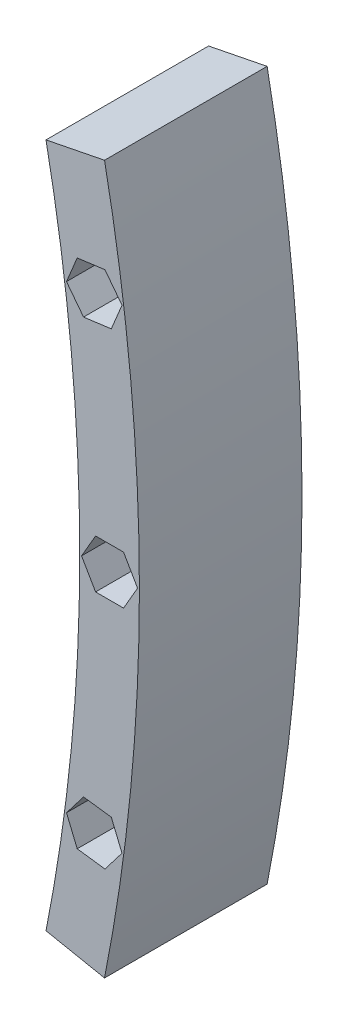
SolidWorks part; units mm, degrees
ref_plane "Front Plane" through (0, 0, 0) normal (0, 0, 1) x (1, 0, 0)
ref_plane "Top Plane" through (0, 0, 0) normal (0, 1, 0) x (1, 0, 0)
ref_plane "Right Plane" through (0, 0, 0) normal (1, 0, 0) x (0, 0, -1)
sketch "Sketch1" plane through (0, 0, 0) normal (0, 0, 1) x (1, 0, 0)
  line L0 (0, 0) -> (226.8966, 0) construction
  line L1 (240, 0) -> (240, 13.4502) construction
  line L2 (239.3239, -47.477) -> (231.4776, -45.9163)
  line L3 (239.3239, 47.477) -> (231.4776, 45.9163)
  line L4 (239.2751, -47.7222) -> (231.4289, -46.1615) construction
  line L5 (202.9378, -135.4484) -> (196.286, -131.0038) construction
  line L6 (202.7989, -135.6562) -> (196.1471, -131.2117) construction
  line L7 (135.6562, -202.7989) -> (131.2117, -196.1471) construction
  line L8 (135.4484, -202.9378) -> (131.0038, -196.286) construction
  line L9 (47.7222, -239.2751) -> (46.1615, -231.4289) construction
  line L10 (47.477, -239.3239) -> (45.9163, -231.4776) construction
  line L11 (-47.477, -239.3239) -> (-45.9163, -231.4776) construction
  line L12 (-47.7222, -239.2751) -> (-46.1615, -231.4289) construction
  line L13 (-135.4484, -202.9378) -> (-131.0038, -196.286) construction
  line L14 (-135.6562, -202.7989) -> (-131.2117, -196.1471) construction
  line L15 (-202.7989, -135.6562) -> (-196.1471, -131.2117) construction
  line L16 (-202.9378, -135.4484) -> (-196.286, -131.0038) construction
  line L17 (-239.2751, -47.7222) -> (-231.4289, -46.1615) construction
  line L18 (-239.3239, -47.477) -> (-231.4776, -45.9163) construction
  line L19 (-239.3239, 47.477) -> (-231.4776, 45.9163) construction
  line L20 (-239.2751, 47.7222) -> (-231.4289, 46.1615) construction
  line L21 (-202.9378, 135.4484) -> (-196.286, 131.0038) construction
  line L22 (-202.7989, 135.6562) -> (-196.1471, 131.2117) construction
  line L23 (-135.6562, 202.7989) -> (-131.2117, 196.1471) construction
  line L24 (-135.4484, 202.9378) -> (-131.0038, 196.286) construction
  line L25 (-47.7222, 239.2751) -> (-46.1615, 231.4289) construction
  line L26 (-47.477, 239.3239) -> (-45.9163, 231.4776) construction
  line L27 (47.477, 239.3239) -> (45.9163, 231.4776) construction
  line L28 (47.7222, 239.2751) -> (46.1615, 231.4289) construction
  line L29 (135.4484, 202.9378) -> (131.0038, 196.286) construction
  line L30 (135.6562, 202.7989) -> (131.2117, 196.1471) construction
  line L31 (202.7989, 135.6562) -> (196.1471, 131.2117) construction
  line L32 (202.9378, 135.4484) -> (196.286, 131.0038) construction
  line L33 (239.2751, 47.7222) -> (231.4289, 46.1615) construction
  line L34 (237.9468, -31.3263) -> (240, 0) construction
  line L35 (236, 0) -> (244, 0) construction
  line L36 (236.8421, 28.6593) -> (235.0847, 30.9495) construction
  line L37 (237.1132, 0) -> (238.5566, -2.5) construction
  line L38 (238.5566, -2.5) -> (241.4434, -2.5) construction
  line L39 (241.4434, -2.5) -> (242.8868, 0) construction
  line L40 (242.8868, 0) -> (241.4434, 2.5) construction
  line L41 (241.4434, 2.5) -> (238.5566, 2.5) construction
  line L42 (238.5566, 2.5) -> (237.1132, 0) construction
  line L43 (235.0847, -30.9495) -> (236.1894, -33.6165) construction
  line L44 (236.1894, -33.6165) -> (239.0515, -33.9933) construction
  line L45 (239.0515, -33.9933) -> (240.8088, -31.7031) construction
  line L46 (240.8088, -31.7031) -> (239.7041, -29.0361) construction
  line L47 (239.7041, -29.0361) -> (236.8421, -28.6593) construction
  line L48 (236.8421, -28.6593) -> (235.0847, -30.9495) construction
  line L55 (239.7041, 29.0361) -> (236.8421, 28.6593) construction
  line L56 (240.8088, 31.7031) -> (239.7041, 29.0361) construction
  line L57 (239.0515, 33.9933) -> (240.8088, 31.7031) construction
  line L58 (236.1894, 33.6165) -> (239.0515, 33.9933) construction
  line L59 (235.0847, 30.9495) -> (236.1894, 33.6165) construction
  line L60 (236.5106, 27.8592) -> (234.2261, 30.8365)
  line L61 (234.2261, 30.8365) -> (235.6622, 34.3036)
  line L62 (235.6622, 34.3036) -> (239.3829, 34.7934)
  line L63 (239.3829, 34.7934) -> (241.6674, 31.8161)
  line L64 (241.6674, 31.8161) -> (240.2313, 28.349)
  line L65 (240.2313, 28.349) -> (236.5106, 27.8592)
  line L66 (241.8764, -3.25) -> (243.7528, 0)
  line L67 (243.7528, 0) -> (241.8764, 3.25)
  line L68 (241.8764, 3.25) -> (238.1236, 3.25)
  line L69 (238.1236, 3.25) -> (236.2472, 0)
  line L70 (236.2472, 0) -> (238.1236, -3.25)
  line L71 (238.1236, -3.25) -> (241.8764, -3.25)
  line L72 (235.6622, -34.3036) -> (239.3829, -34.7934)
  line L73 (239.3829, -34.7934) -> (241.6674, -31.8161)
  line L74 (241.6674, -31.8161) -> (240.2313, -28.349)
  line L75 (240.2313, -28.349) -> (236.5106, -27.8592)
  line L76 (236.5106, -27.8592) -> (234.2261, -30.8365)
  line L77 (234.2261, -30.8365) -> (235.6622, -34.3036)
  arc A0 (239.3239, -47.477) -> (239.3239, 47.477) centre (0.6407, 0) ccw
  arc A1 (231.4776, -45.9163) -> (231.4776, 45.9163) centre (0.6407, 0) ccw
  arc A2 (196.286, -131.0038) -> (231.4289, -46.1615) centre (0.592, -0.2452) ccw construction
  arc A3 (202.9378, -135.4484) -> (239.2751, -47.7222) centre (0.592, -0.2452) ccw construction
  arc A4 (131.2117, -196.1471) -> (196.1471, -131.2117) centre (0.4531, -0.4531) ccw construction
  arc A5 (135.6562, -202.7989) -> (202.7989, -135.6562) centre (0.4531, -0.4531) ccw construction
  arc A6 (46.1615, -231.4289) -> (131.0038, -196.286) centre (0.2452, -0.592) ccw construction
  arc A7 (47.7222, -239.2751) -> (135.4484, -202.9378) centre (0.2452, -0.592) ccw construction
  arc A8 (-45.9163, -231.4776) -> (45.9163, -231.4776) centre (0, -0.6407) ccw construction
  arc A9 (-47.477, -239.3239) -> (47.477, -239.3239) centre (0, -0.6407) ccw construction
  arc A10 (-131.0038, -196.286) -> (-46.1615, -231.4289) centre (-0.2452, -0.592) ccw construction
  arc A11 (-135.4484, -202.9378) -> (-47.7222, -239.2751) centre (-0.2452, -0.592) ccw construction
  arc A12 (-196.1471, -131.2117) -> (-131.2117, -196.1471) centre (-0.4531, -0.4531) ccw construction
  arc A13 (-202.7989, -135.6562) -> (-135.6562, -202.7989) centre (-0.4531, -0.4531) ccw construction
  arc A14 (-231.4289, -46.1615) -> (-196.286, -131.0038) centre (-0.592, -0.2452) ccw construction
  arc A15 (-239.2751, -47.7222) -> (-202.9378, -135.4484) centre (-0.592, -0.2452) ccw construction
  arc A16 (-231.4776, 45.9163) -> (-231.4776, -45.9163) centre (-0.6407, 0) ccw construction
  arc A17 (-239.3239, 47.477) -> (-239.3239, -47.477) centre (-0.6407, 0) ccw construction
  arc A18 (-196.286, 131.0038) -> (-231.4289, 46.1615) centre (-0.592, 0.2452) ccw construction
  arc A19 (-202.9378, 135.4484) -> (-239.2751, 47.7222) centre (-0.592, 0.2452) ccw construction
  arc A20 (-131.2117, 196.1471) -> (-196.1471, 131.2117) centre (-0.4531, 0.4531) ccw construction
  arc A21 (-135.6562, 202.7989) -> (-202.7989, 135.6562) centre (-0.4531, 0.4531) ccw construction
  arc A22 (-46.1615, 231.4289) -> (-131.0038, 196.286) centre (-0.2452, 0.592) ccw construction
  arc A23 (-47.7222, 239.2751) -> (-135.4484, 202.9378) centre (-0.2452, 0.592) ccw construction
  arc A24 (45.9163, 231.4776) -> (-45.9163, 231.4776) centre (0, 0.6407) ccw construction
  arc A25 (47.477, 239.3239) -> (-47.477, 239.3239) centre (0, 0.6407) ccw construction
  arc A26 (131.0038, 196.286) -> (46.1615, 231.4289) centre (0.2452, 0.592) ccw construction
  arc A27 (135.4484, 202.9378) -> (47.7222, 239.2751) centre (0.2452, 0.592) ccw construction
  arc A28 (196.1471, 131.2117) -> (131.2117, 196.1471) centre (0.4531, 0.4531) ccw construction
  arc A29 (202.7989, 135.6562) -> (135.6562, 202.7989) centre (0.4531, 0.4531) ccw construction
  arc A30 (231.4289, 46.1615) -> (196.286, 131.0038) centre (0.592, 0.2452) ccw construction
  arc A31 (239.2751, 47.7222) -> (202.9378, 135.4484) centre (0.592, 0.2452) ccw construction
  circle A34 centre (240, 0) radius 2.5 construction
  circle A35 centre (237.9468, -31.3263) radius 2.5 construction
  point P0 (240, 0)
  point P101 (0, 0)
  dimension "D1" = 8
  dimension "D2" = 16
  dimension "D3" = 0.25
  dimension "D4" = 7.5
  dimension "D5" = 5
  dimension "D6" = 5
  dimension "D7" = 0.75
extrude "Boss-Extrude1" add sketch "Sketch1" along normal blind 21.8
